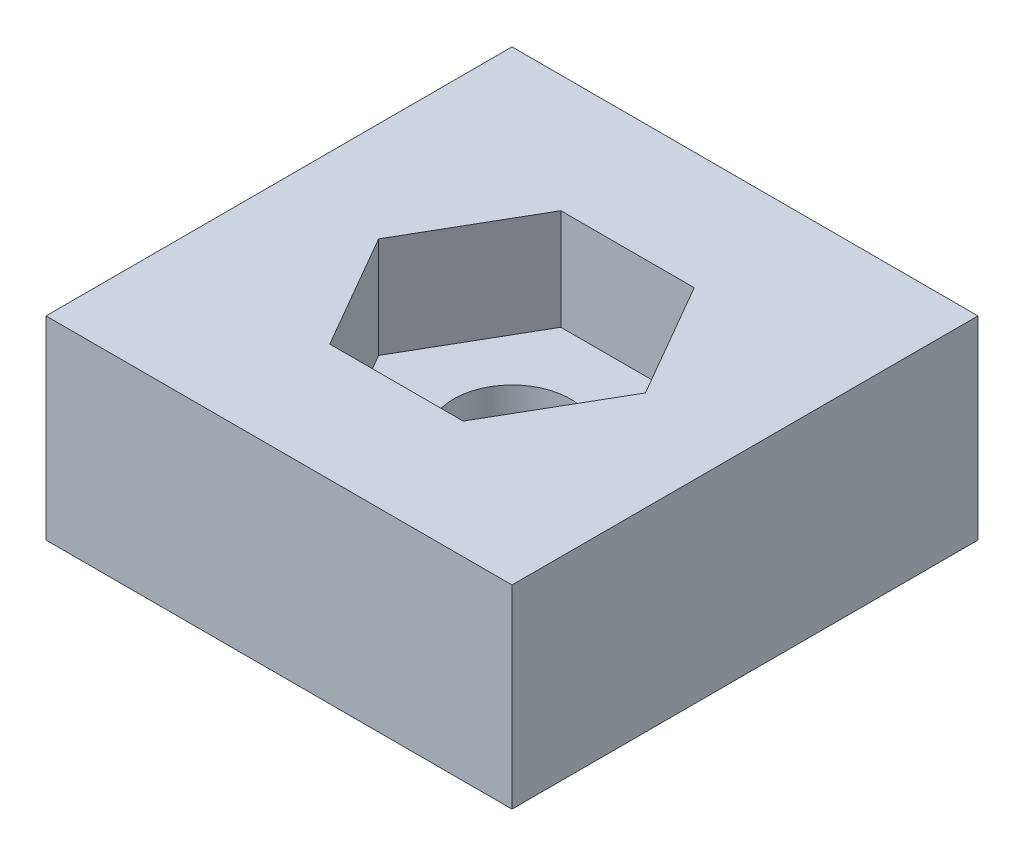
SolidWorks part; units mm, degrees
ref_plane "Front Plane" through (0, 0, 0) normal (0, 0, 1) x (1, 0, 0)
ref_plane "Top Plane" through (0, 0, 0) normal (0, 1, 0) x (1, 0, 0)
ref_plane "Right Plane" through (0, 0, 0) normal (1, 0, 0) x (0, 0, -1)
sketch "Sketch1" plane through (0, 0, 0) normal (0, 1, 0) x (1, 0, 0)
  line L1 (-6, -6) -> (6, -6)
  line L2 (-6, -6) -> (-6, 6)
  line L3 (-6, 6) -> (6, 6)
  line L4 (6, -6) -> (6, 6)
  line L5 (-6, -6) -> (6, 6) construction
  line L6 (-6, 6) -> (6, -6) construction
  point P0 (0, 0)
  dimension "D1" = 12
  dimension "D2" = 12
extrude "Boss-Extrude1" add sketch "Sketch1" along normal blind 5
sketch "Sketch2" plane through (0, 5, 0) normal (0, 1, 0) x (1, 0, 0)
  circle A0 centre (0, 0) radius 1.5
  dimension "D1" = 3
extrude "Cut-Extrude1" cut sketch "Sketch2" against normal blind 5
sketch "Sketch3" plane through (0, 5, 0) normal (0, 1, 0) x (1, 0, 0)
  line L1 (3.4352, 0) -> (1.7176, 2.975)
  line L2 (1.7176, 2.975) -> (-1.7176, 2.975)
  line L3 (-1.7176, 2.975) -> (-3.4352, 0)
  line L4 (-3.4352, 0) -> (-1.7176, -2.975)
  line L5 (-1.7176, -2.975) -> (1.7176, -2.975)
  line L6 (1.7176, -2.975) -> (3.4352, 0)
  circle A0 centre (0, 0) radius 2.975 construction
  dimension "D1" = 5.95
extrude "Cut-Extrude2" cut sketch "Sketch3" against normal blind 2.6
